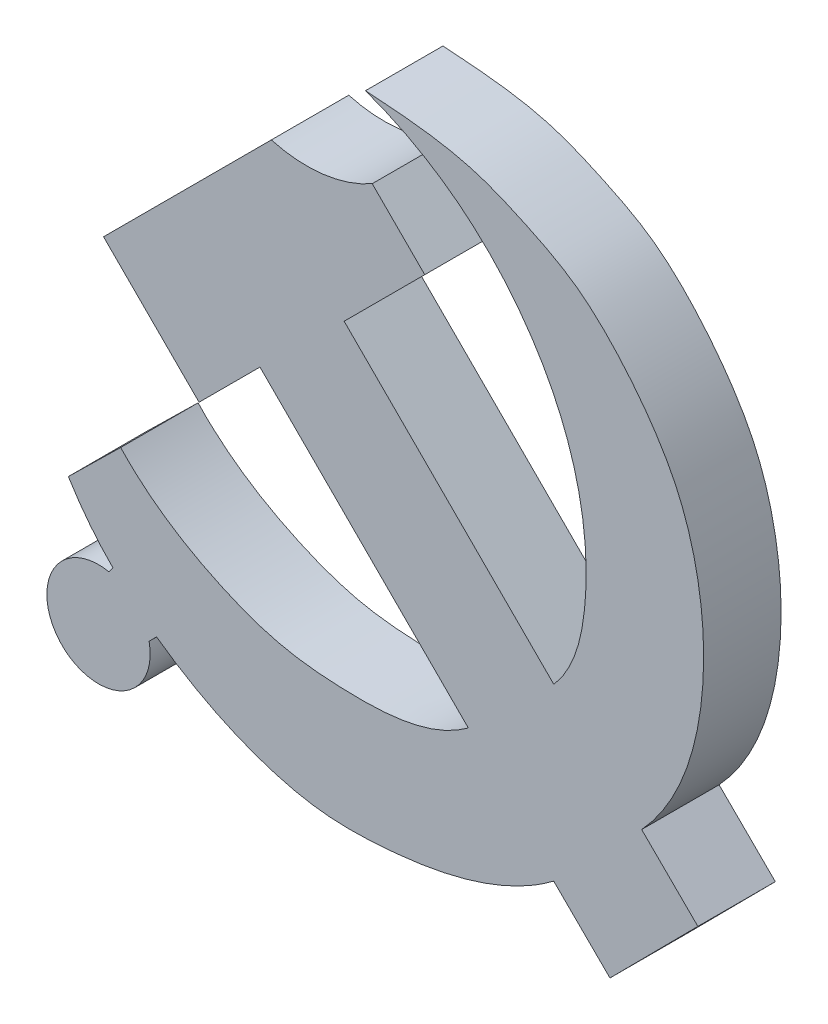
SolidWorks part; units mm, degrees
other "相机1"
ref_plane "Front" through (0, 0, 0) normal (0, 0, 1) x (1, 0, 0)
ref_plane "Top" through (0, 0, 0) normal (0, 1, 0) x (1, 0, 0)
ref_plane "Right" through (0, 0, 0) normal (1, 0, 0) x (0, 0, -1)
sketch "草图1" plane through (0, 0, 0) normal (0, 0, 1) x (1, 0, 0)
  line L0 (200, 411) -> (1000, 411) construction
  line L1 (86.6539, -86.6539) -> (-86.6539, 86.6539) construction
  line L3 (-16.3116, -16.3116) -> (15.8383, 15.8383) construction
  point P6 (0, 0)
  line B0 (-89.5504, 9.7433) -> (-65.9584, 33.3353)
  line B1 (-65.9584, 33.3353) -> (14.7631, -47.3863)
  line B2 (-89.5504, 9.7433) -> (-126.5575, 46.7504)
  line B3 (-126.5575, 46.7504) -> (-61.5639, 111.744)
  line B4 (-22.4752, 116.6011) -> (-2.1213, 96.2473)
  line B5 (-2.1213, 96.2473) -> (-33.346, 65.0226)
  line B6 (-33.346, 65.0226) -> (47.8382, -16.1616)
  line B7 (47.8382, -82.2246) -> (69.6221, -103.828)
  line B8 (69.6221, -103.828) -> (103.6858, -69.4798)
  line B9 (103.6858, -69.4798) -> (81.9019, -47.8764)
  line B10 (-122.9521, -62.464) -> (-124.5115, -64.5918)
  line B11 (-106.0187, -77.2023) -> (-108.9098, -80.1175)
  line B12 (-119.9282, -20.6344) -> (-140.199, -40.5133)
  arc B13 (-61.5639, 111.744) -> (-22.4752, 116.6011) centre (-47.8385, 161.0017) ccw
  arc B14 (-124.5115, -64.5918) -> (-108.9098, -80.1175) centre (-128.502, -84.2038) ccw
  spline B15 degree 3 poles (-25.0959, 146.4846) (-8.9632, 140.7547) (13.873, 127.0365) (36.1007, 101.7454) (48.6697, 80.9532) (56.8253, 59.4823) (60.5194, 37.9959) (60.5218, 11.9494) (56.2937, -6.6936) (47.8382, -16.1616) knots 0 0 0 0 0.253919 0.386919 0.496447 0.61318 0.725931 0.817885 1 1 1 1
  spline B16 degree 3 poles (14.7631, -47.3863) (0.4944, -57.8923) (-24.857, -59.6898) (-58.1867, -56.8512) (-88.6922, -45.3823) (-109.0755, -32.1995) (-119.9282, -20.6344) knots 0 0 0 0 0.341116 0.507979 0.680177 1 1 1 1
  spline B17 degree 2 poles (-140.199, -40.5133) (-132.851, -52.4888) (-122.9521, -62.464) knots 0 0 0 1 1 1
  spline B18 degree 3 poles (-106.0187, -77.2023) (-93.7149, -86.0316) (-72.9291, -97.233) (-42.0775, -104.9124) (-17.0248, -104.2234) (14.0567, -100.072) (36.0087, -91.1437) (47.8382, -82.2246) knots 0 0 0 0 0.27636 0.427879 0.575006 0.73144 1 1 1 1
  spline B19 degree 3 poles (-25.0959, 146.4846) (-10.5671, 145.4981) (11.1606, 144.0728) (37.5313, 132.5834) (55.8976, 123.3328) (71.5372, 108.6726) (84.7105, 92.5426) (97.2525, 72.1557) (105.2763, 44.8158) (107.6034, 1.7223) (97.1118, -31.4576) (81.9019, -47.8764) knots 0 0 0 0 0.159869 0.2292 0.310741 0.380983 0.459297 0.536186 0.638542 0.764116 1 1 1 1
sketch_block_instance "块1-1"
sketch_block "块1"
extrude "凸台-拉伸1" add sketch "草图1" along normal blind 30
